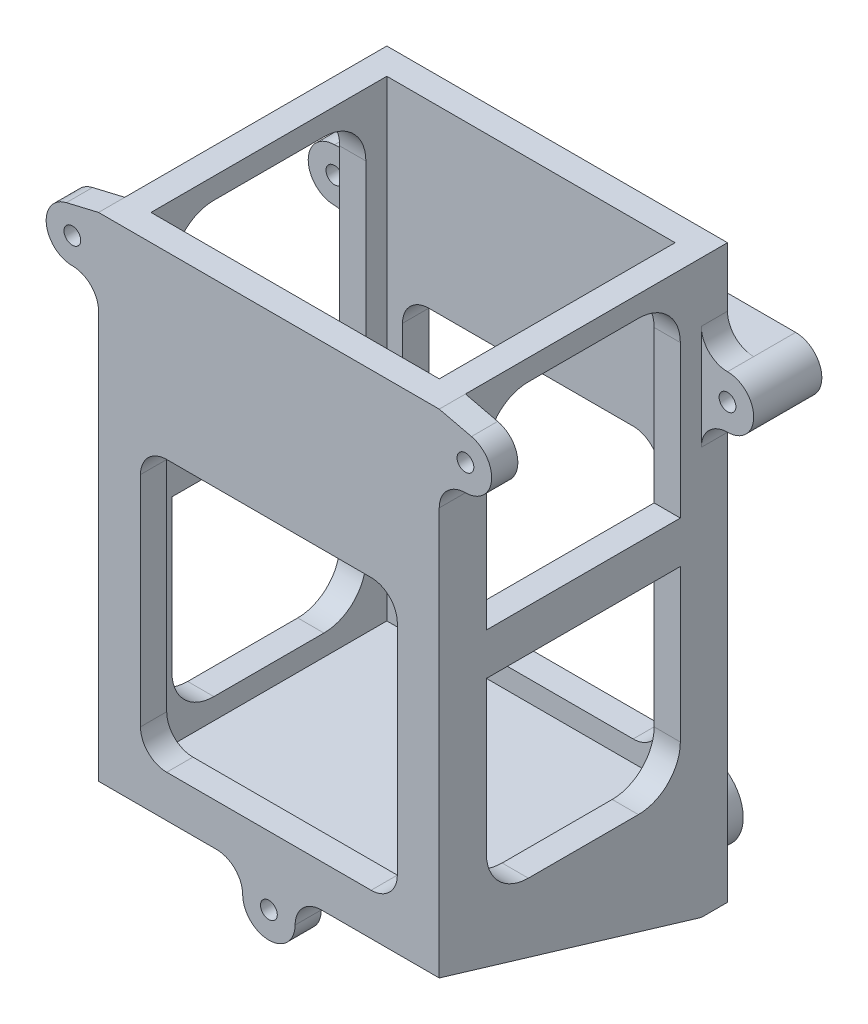
SolidWorks part; units mm, degrees
ref_plane "前视基准面" through (0, 0, 0) normal (0, 0, 1) x (1, 0, 0)
ref_plane "上视基准面" through (0, 0, 0) normal (0, 1, 0) x (1, 0, 0)
ref_plane "右视基准面" through (0, 0, 0) normal (1, 0, 0) x (0, 0, -1)
sketch "草图1" plane through (0, 0, 0) normal (0, 1, 0) x (1, 0, 0)
  line L0 (5, 5) -> (60, 5)
  line L1 (0, 0) -> (65, 0)
  line L2 (0, 0) -> (0, 55)
  line L3 (0, 55) -> (65, 55)
  line L4 (65, 0) -> (65, 55)
  line L5 (60, 5) -> (60, 50)
  line L6 (5, 50) -> (60, 50)
  line L7 (5, 5) -> (5, 50)
  dimension "D1" = 65
  dimension "D2" = 55
  dimension "D3" = 5
extrude "凸台-拉伸1" add sketch "草图1" along normal blind 90
sketch "草图2" plane through (0, 0, 0) normal (0, -1, 0) x (1, 0, 0)
  line L1 (0, 0) -> (65, 0)
  line L2 (0, 0) -> (0, -55)
  line L3 (0, -55) -> (65, -55)
  line L4 (65, 0) -> (65, -55)
extrude "凸台-拉伸2" add sketch "草图2" along normal blind 4
sketch "草图3" plane through (0, 0, -55) normal (0, 0, -1) x (-1, 0, 0)
  line L1 (-65, -4) -> (0, -4)
  line L2 (-65, -4) -> (-65, -19)
  line L3 (-65, -19) -> (0, -19)
  line L4 (0, -4) -> (0, -19)
  dimension "D1" = 15
extrude "凸台-拉伸3" add sketch "草图3" against normal blind 5
sketch "草图4" plane through (65, 0, 0) normal (1, 0, 0) x (0, 0, -1)
  line L0 (0, -4) -> (50, -19)
  line L1 (50, -19) -> (50, -4)
  line L2 (50, -4) -> (0, -4)
extrude "凸台-拉伸4" add sketch "草图4" against normal blind 5
sketch "草图5" plane through (0, 0, 0) normal (-1, 0, 0) x (0, 0, 1)
  line L0 (-50, -19) -> (0, -4)
  line L1 (0, -4) -> (-50, -4)
  line L2 (-50, -4) -> (-50, -19)
extrude "凸台-拉伸5" add sketch "草图5" against normal blind 5
sketch "草图6" plane through (0, 0, -55) normal (0, 0, -1) x (-1, 0, 0)
  line L0 (-32.5, -19) -> (-32.5, 49.1223) construction
  line L1 (-65, -19) -> (0, -19) construction
  line L2 (-88.2543, -11.5) -> (15.5111, -11.5) construction
  circle A0 centre (-12.5, -11.5) radius 1.6
  circle A1 centre (-52.5, -11.5) radius 1.6
  dimension "D2" = 3.2
  dimension "D3" = 3.2
  dimension "D5" = 20
  dimension "D1" = 7.5
  dimension "D4" = 20
extrude "切除-拉伸1" cut sketch "草图6" against normal through all
sketch "草图7" plane through (0, 0, -55) normal (0, 0, -1) x (-1, 0, 0)
  line L0 (-12.5, -11.5) -> (-12.5, 68.68) construction
  line L1 (-12.5, 68.68) -> (5, 68.68) construction
  line L2 (0, 90) -> (0, -19) construction
  line L3 (0, 78.68) -> (0, 58.68)
  line L4 (-32.5, 90) -> (-32.5, 49.3441) construction
  line L5 (-65, 90) -> (0, 90) construction
  line L6 (-52.5, 68.68) -> (-70, 68.68) construction
  line L7 (-65, 78.68) -> (-65, 58.68)
  circle A0 centre (5, 68.68) radius 1.6
  arc A1 (5, 63.68) -> (5, 73.68) centre (5, 68.68) ccw
  arc A2 (0, 78.68) -> (5, 73.68) centre (5, 78.68) ccw
  arc A3 (0, 58.68) -> (5, 63.68) centre (5, 58.68) cw
  arc A4 (-65, 58.68) -> (-70, 63.68) centre (-70, 58.68) ccw
  arc A5 (-65, 78.68) -> (-70, 73.68) centre (-70, 78.68) cw
  arc A6 (-70, 63.68) -> (-70, 73.68) centre (-70, 68.68) cw
  circle A7 centre (-70, 68.68) radius 1.6
  dimension "D3" = 3.2
  dimension "D4" = 10
  dimension "D1" = 80.18
  dimension "D2" = 17.5
extrude "凸台-拉伸6" add sketch "草图7" against normal blind 5
sketch "草图8" plane through (0, 0, 0) normal (0, 0, 1) x (1, 0, 0)
  line L0 (70, 68.68) -> (70, 83.68) construction
  line L1 (71.1504, 88.5459) -> (65, 90)
  line L2 (65, 90) -> (65, -4) construction
  line L3 (65, 90) -> (65, 73.68)
  line L4 (32.5, 90) -> (32.5, 60.6114) construction
  line L5 (0, 90) -> (65, 90) construction
  line L6 (-5, 68.68) -> (-5, 83.68) construction
  line L7 (0, 90) -> (0, 73.68)
  line L8 (-6.1504, 88.5459) -> (0, 90)
  line L9 (5, -4) -> (60, -4) construction
  line L10 (60, -4) -> (5, -4) construction
  line L11 (42.5, -4) -> (22.5, -4)
  circle A0 centre (70, 83.68) radius 1.6
  arc A1 (70, 78.68) -> (71.1504, 88.5459) centre (70, 83.68) ccw
  arc A2 (70, 78.68) -> (65, 73.68) centre (70, 73.68) ccw
  arc A3 (-5, 78.68) -> (0, 73.68) centre (-5, 73.68) cw
  arc A4 (-5, 78.68) -> (-6.1504, 88.5459) centre (-5, 83.68) cw
  circle A5 centre (-5, 83.68) radius 1.6
  arc A6 (27.5, -9) -> (37.5, -9) centre (32.5, -9) ccw
  arc A7 (42.5, -4) -> (37.5, -9) centre (42.5, -9) ccw
  arc A8 (27.5, -9) -> (22.5, -4) centre (22.5, -9) ccw
  circle A9 centre (32.5, -9) radius 1.6
  dimension "D2" = 3.2
  dimension "D3" = 10
  dimension "D4" = 10
  dimension "D5" = 32.5
  dimension "D8" = 3.2
  dimension "D1" = 15
  dimension "D6" = 10
  dimension "D7" = 10
extrude "凸台-拉伸7" add sketch "草图8" against normal blind 5
sketch "草图9" plane through (0, 0, -55) normal (0, 0, -1) x (-1, 0, 0)
  line L0 (-70, 73.68) -> (5, 73.68)
  line L1 (-70, 63.68) -> (5, 63.68)
  arc A0 (-70, 73.68) -> (-70, 63.68) centre (-70, 68.68) ccw
  arc A1 (5, 63.68) -> (5, 73.68) centre (5, 68.68) ccw
  circle A2 centre (5, 68.68) radius 1.6
  circle A3 centre (-70, 68.68) radius 1.6
  circle A4 centre (-52.5, -11.5) radius 7.5
  circle A5 centre (-52.5, -11.5) radius 1.6
  circle A6 centre (-12.5, -11.5) radius 1.6
  circle A7 centre (-12.5, -11.5) radius 7.5
  dimension "D1" = 15
  dimension "D2" = 15
extrude "凸台-拉伸9" add sketch "草图9" along normal blind 8
sketch "草图10" plane through (0, 0, -55) normal (0, 0, -1) x (-1, 0, 0)
  line L6 (-57, 55.68) -> (-57, 4)
  line L7 (-57, 4) -> (-8, 4)
  line L8 (-8, 55.68) -> (-8, 4)
  line L9 (-57, 55.68) -> (-8, 55.68)
extrude "切除-拉伸2" cut sketch "草图10" against normal through all
sketch "草图12" plane through (0, 0, 0) normal (-1, 0, 0) x (0, 0, 1)
  line L0 (-46, 86) -> (-46, 49)
  line L1 (-46, 45) -> (-9, 45) construction
  line L2 (-46, 41) -> (-9, 41)
  line L3 (-46, 49) -> (-9, 49)
  line L4 (-9, 41) -> (-9, 4)
  line L5 (-46, 4) -> (-9, 4)
  line L6 (-9, 86) -> (-9, 49)
  line L7 (-46, 86) -> (-9, 86)
  line L8 (-46, 41) -> (-46, 4)
  dimension "D1" = 4
  dimension "D2" = 4
extrude "切除-拉伸3" cut sketch "草图12" against normal through all
fillet "圆角2" radius 8 8 edges at (62.5, 4, -46) (62.5, 4, -9) (2.5, 4, -46) (2.5, 4, -9) (2.5, 86, -9) (2.5, 86, -46) (62.5, 86, -46) (62.5, 86, -9)
fillet "圆角3" radius 5 8 edges at (8, 55.68, -52.5) (57, 55.68, -52.5) (57, 4, -52.5) (8, 4, -52.5) (57, 55.68, -2.5) (8, 55.68, -2.5) (8, 4, -2.5) (57, 4, -2.5)
